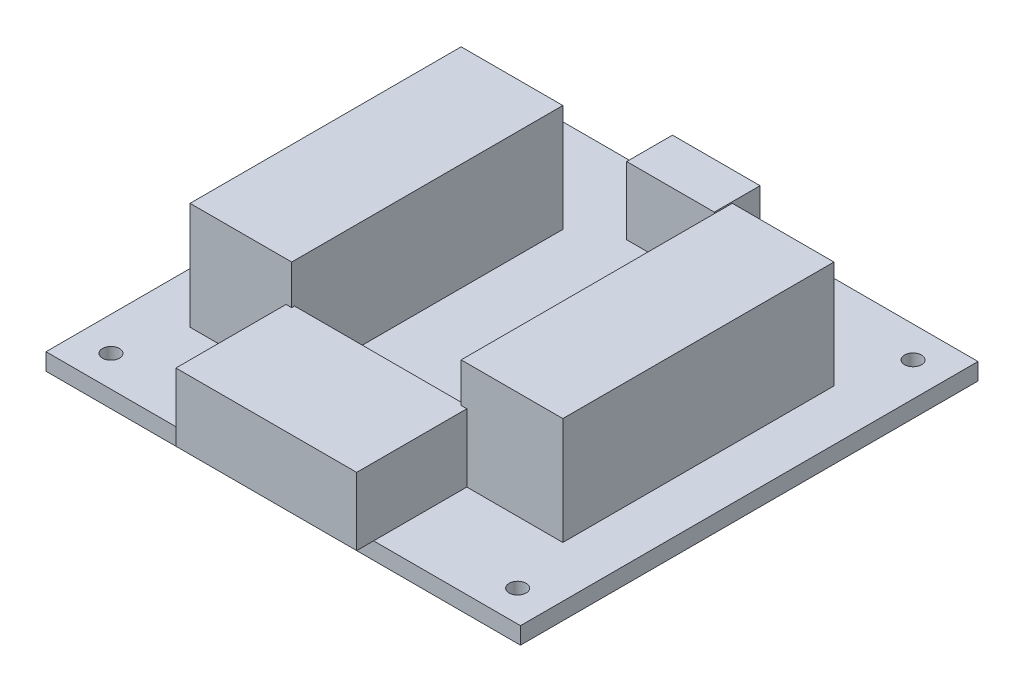
SolidWorks part; units mm, degrees
ref_plane "Front Plane" through (0, 0, 0) normal (0, 0, 1) x (1, 0, 0)
ref_plane "Top Plane" through (0, 0, 0) normal (0, 1, 0) x (1, 0, 0)
ref_plane "Right Plane" through (0, 0, 0) normal (1, 0, 0) x (0, 0, -1)
sketch "Sketch1" plane through (0, 0, 0) normal (0, 1, 0) x (1, 0, 0)
  line L1 (-42, 40.5) -> (42, 40.5)
  line L2 (-42, 40.5) -> (-42, -40.5)
  line L3 (-42, -40.5) -> (42, -40.5)
  line L4 (42, 40.5) -> (42, -40.5)
  line L5 (-42, 40.5) -> (42, -40.5) construction
  line L6 (-42, -40.5) -> (42, 40.5) construction
  point P0 (0, 0)
  dimension "D1" = 84
  dimension "D2" = 81
extrude "Boss-Extrude1" add sketch "Sketch1" along normal blind 3
sketch "Sketch2" plane through (0, 3, 0) normal (0, 1, 0) x (1, 0, 0)
  line L0 (-1.65, 0) -> (1.65, 0) construction
  line L1 (-33, 24) -> (-15, 24)
  line L2 (-33, 24) -> (-33, -24)
  line L3 (-33, -24) -> (-15, -24)
  line L4 (-15, 24) -> (-15, -24)
  line L5 (-33, 24) -> (-15, -24) construction
  line L6 (-33, -24) -> (-15, 24) construction
  line L7 (0, -1.65) -> (0, 1.65) construction
  line L8 (0, 38.8255) -> (0, -30.2619) construction
  line L9 (33, -24) -> (15, 24) construction
  line L10 (33, 24) -> (15, -24) construction
  line L11 (15, 24) -> (15, -24)
  line L12 (33, -24) -> (15, -24)
  line L13 (33, 24) -> (33, -24)
  line L14 (33, 24) -> (15, 24)
  point P0 (-24, 0)
  point P16 (24, 0)
  dimension "D1" = 18
  dimension "D2" = 48
  dimension "D3" = 33
extrude "Boss-Extrude2" add sketch "Sketch2" along normal blind 19
sketch "Sketch3" plane through (0, 3, 0) normal (0, 1, 0) x (1, 0, 0)
  line L0 (0, -12.1) -> (0, 12.1) construction
  line L1 (-16, -23.5) -> (16, -23.5)
  line L2 (-16, -23.5) -> (-16, -43.5)
  line L3 (-16, -43.5) -> (16, -43.5)
  line L4 (16, -23.5) -> (16, -43.5)
  line L5 (-16, -23.5) -> (16, -43.5) construction
  line L6 (-16, -43.5) -> (16, -23.5) construction
  line L7 (-42, -40.5) -> (42, -40.5) construction
  line L9 (-7.7535, 36.1639) -> (7.7535, 36.1639)
  line L10 (-7.7535, 36.1639) -> (-7.7535, 28.0632)
  line L11 (-7.7535, 28.0632) -> (7.7535, 28.0632)
  line L12 (7.7535, 36.1639) -> (7.7535, 28.0632)
  line L13 (-7.7535, 36.1639) -> (7.7535, 28.0632) construction
  line L14 (-7.7535, 28.0632) -> (7.7535, 36.1639) construction
  point P0 (0, -33.5)
  point P9 (0, 32.1135)
  dimension "D1" = 20
  dimension "D2" = 3
  dimension "D3" = 32
extrude "Boss-Extrude3" add sketch "Sketch3" along normal blind 12
sketch "Sketch4" plane through (0, 3, 0) normal (0, 1, 0) x (1, 0, 0)
  line L1 (-36, 35) -> (36, 35) construction
  line L2 (-36, 35) -> (-36, -35) construction
  line L3 (-36, -35) -> (36, -35) construction
  line L4 (36, 35) -> (36, -35) construction
  line L5 (-36, 35) -> (36, -35) construction
  line L6 (-36, -35) -> (36, 35) construction
  circle A0 centre (-36, 35) radius 1.5
  circle A1 centre (36, 35) radius 1.5
  circle A2 centre (36, -35) radius 1.5
  circle A3 centre (-36, -35) radius 1.5
  point P0 (0, 0)
  dimension "D1" = 3
  dimension "D2" = 72
  dimension "D3" = 70
extrude "Cut-Extrude1" cut sketch "Sketch4" against normal blind 12
